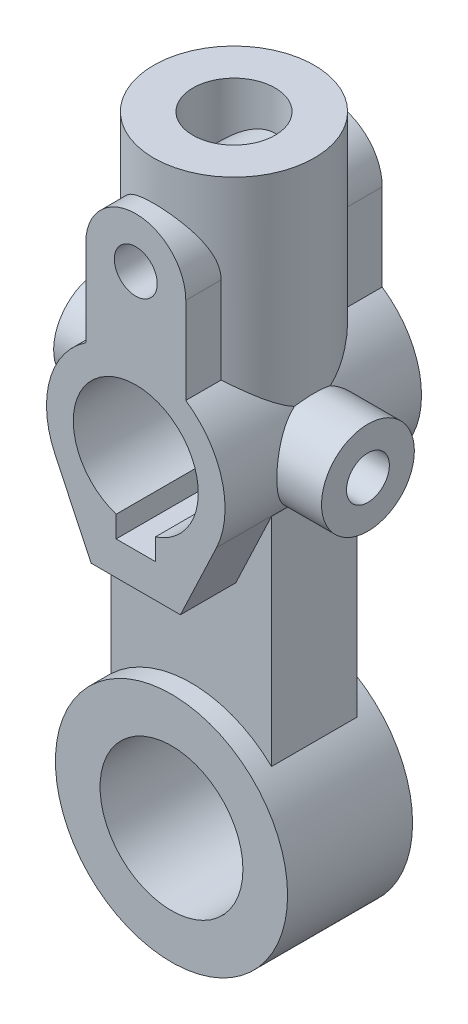
SolidWorks part; units mm, degrees
ref_plane "Alzado" through (0, 0, 0) normal (0, 0, 1) x (1, 0, 0)
ref_plane "Planta" through (0, 0, 0) normal (0, 1, 0) x (1, 0, 0)
ref_plane "Vista lateral" through (0, 0, 0) normal (1, 0, 0) x (0, 0, -1)
sketch "Croquis1" plane through (0, 0, 0) normal (0, 0, 1) x (1, 0, 0)
  circle A0 centre (0, 0) radius 32.5
  circle A1 centre (0, 0) radius 20
  dimension "D1" = 65
  dimension "D2" = 40
extrude "Saliente-Extruir1" add sketch "Croquis1" along normal mid plane 35
sketch "Croquis2" plane through (0, 0, 0) normal (0, 0, 1) x (1, 0, 0)
  line L0 (-5.5, 72.3868) -> (5.5, 72.3868)
  line L1 (5.5, 72.3868) -> (5.5, 78.3868)
  line L2 (-5.5, 72.3868) -> (-5.5, 78.3868)
  line L3 (0, 95) -> (0, 140) construction
  line L4 (-12.5, 63) -> (12.5, 63)
  line L5 (12.5, 63) -> (22.5914, 84.2935)
  line L6 (-14, 115.7123) -> (-14, 140)
  line L7 (14, 115.7123) -> (14, 140)
  line L8 (-12.5, 63) -> (-22.5914, 84.2935)
  arc A0 (5.5, 78.3868) -> (-5.5, 78.3868) centre (0, 95) ccw
  arc A1 (-14, 115.7123) -> (-22.5914, 84.2935) centre (0, 95) ccw
  circle A2 centre (0, 140) radius 6
  arc A3 (14, 140) -> (-14, 140) centre (0, 140) ccw
  arc A4 (22.5914, 84.2935) -> (14, 115.7123) centre (0, 95) ccw
  point P3 (0, 117.5)
  point P5 (0, 72.3868)
  point P14 (34.7946, 105.2488)
  point P16 (0, 63)
  point P20 (-29.4468, 96.8886)
  point P21 (-35.167, 103.9288)
  dimension "D1" = 35
  dimension "D2" = 50
  dimension "D6" = 14
  dimension "D8" = 12
  dimension "D3" = 95
  dimension "D4" = 11
  dimension "D5" = 6
  dimension "D7" = 45
  dimension "D9" = 25
  dimension "D10" = 32
extrude "Saliente-Extruir2" add sketch "Croquis2" along normal mid plane 55 separate body
sketch "Croquis3" plane through (0, 0, 0) normal (0, 0, 1) x (1, 0, 0)
  line L0 (-22.5, 84.1007) -> (-22.5, 23.4521)
  line L1 (-22.5914, 84.2935) -> (-12.5, 63) construction
  line L2 (22.5, 84.1007) -> (22.5, 23.4521)
  line L3 (12.5, 63) -> (22.5914, 84.2935) construction
  line L5 (22.5, 84.1007) -> (12.5, 63)
  line L6 (12.5, 63) -> (-12.5, 63)
  line L7 (-12.5, 63) -> (-22.5, 84.1007)
  circle A0 centre (0, 0) radius 32.5 construction
  arc A1 (22.5, 23.4521) -> (-22.5, 23.4521) centre (0, 0) ccw
  dimension "D1" = 22.5
  dimension "D2" = 45
extrude "Saliente-Extruir3" add sketch "Croquis3" along normal mid plane 24
ref_plane "Plano1" through (0, 165, 0) normal (0, 1, 0) x (1, 0, 0)
sketch "Croquis4" plane through (0, 165, 0) normal (0, 1, 0) x (1, 0, 0)
  circle A0 centre (0, 0) radius 22.5
  circle A1 centre (0, 0) radius 11.5
  dimension "D1" = 23
  dimension "D2" = 45
extrude "Saliente-Extruir4" add sketch "Croquis4" against normal up to next
sketch "Croquis5" plane through (0, 0, 0) normal (1, 0, 0) x (0, 0, -1)
  line L3 (27.5, 112.5) -> (-27.5, 112.5) construction
  line L4 (0, 112.5) -> (0, 95) construction
  circle A0 centre (0, 95) radius 13
  circle A1 centre (0, 95) radius 6
  dimension "D2" = 12
  dimension "D3" = 26
  dimension "D1" = 17.5
extrude "Saliente-Extruir5" add sketch "Croquis5" along normal mid plane 75
sketch "Croquis6" plane through (0, 0, 27.5) normal (0, 0, 1) x (1, 0, 0)
  line L0 (5.5, 72.3868) -> (5.5, 78.3868) construction
  line L1 (5.5, 72.3868) -> (5.5, 78.3868)
  line L2 (-5.5, 72.3868) -> (5.5, 72.3868) construction
  line L3 (-5.5, 72.3868) -> (5.5, 72.3868)
  line L4 (-5.5, 78.3868) -> (-5.5, 72.3868) construction
  line L5 (-5.5, 78.3868) -> (-5.5, 72.3868)
  arc A0 (5.5, 78.3868) -> (-5.5, 78.3868) centre (0, 95) ccw construction
  arc A1 (5.5, 78.3868) -> (-5.5, 78.3868) centre (0, 95) ccw
extrude "Cortar-Extruir1" cut sketch "Croquis6" against normal through all
sketch "Croquis7" plane through (37.5, 0, 0) normal (1, 0, 0) x (0, 0, -1)
  circle A0 centre (0, 95) radius 6 construction
  circle A1 centre (0, 95) radius 6
extrude "Cortar-Extruir2" cut sketch "Croquis7" against normal through all
